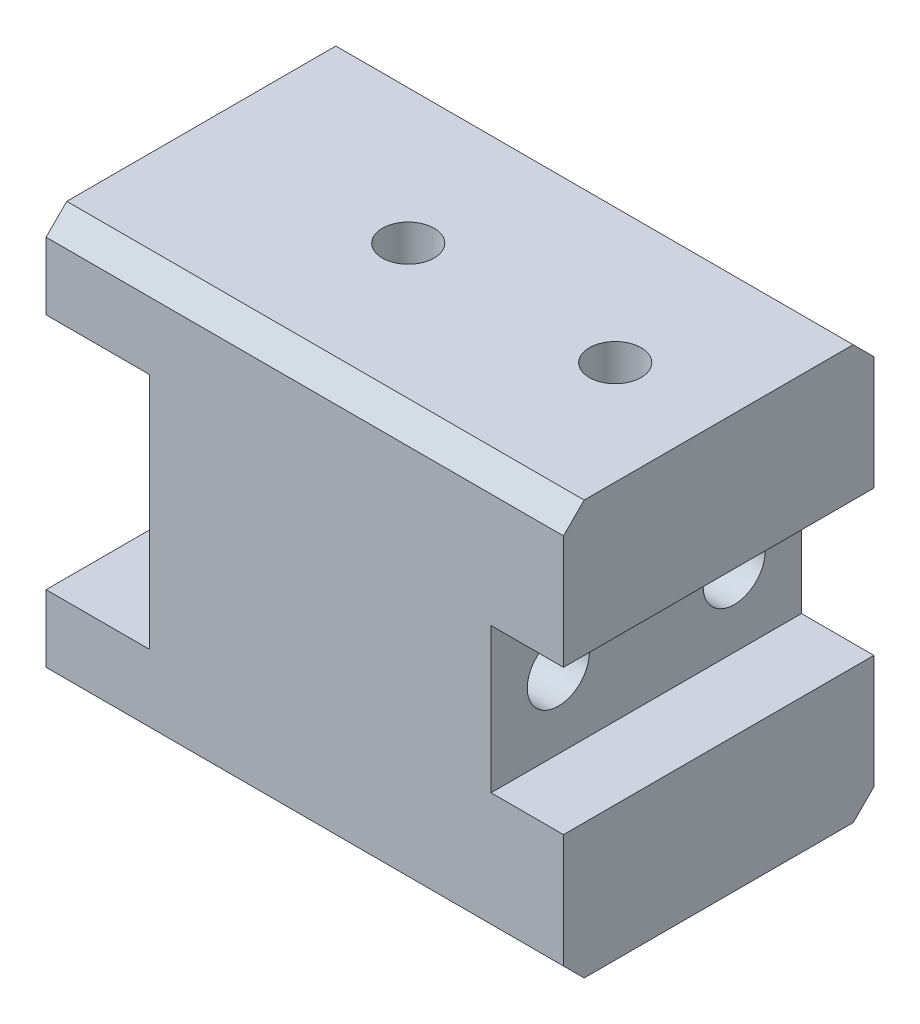
SolidWorks part; units mm, degrees
ref_plane "Front" through (0, 0, 0) normal (0, 0, 1) x (1, 0, 0)
ref_plane "Top" through (0, 0, 0) normal (0, 1, 0) x (1, 0, 0)
ref_plane "Right" through (0, 0, 0) normal (1, 0, 0) x (0, 0, -1)
sketch "草图1" plane through (0, 0, 0) normal (1, 0, 0) x (0, 0, -1)
  line L1 (7.5, -10) -> (-7.5, -10)
  line L2 (7.5, -10) -> (7.5, 10)
  line L3 (7.5, 10) -> (-7.5, 10)
  line L4 (-7.5, -10) -> (-7.5, 10)
  line L5 (7.5, -10) -> (-7.5, 10) construction
  line L6 (7.5, 10) -> (-7.5, -10) construction
  point P0 (0, 0)
  dimension "D1" = 15
  dimension "D2" = 20
extrude "凸台-拉伸1" add sketch "草图1" along normal blind 25
sketch "草图2" plane through (0, 0, 0) normal (-1, 0, 0) x (0, 0, 1)
  line L0 (-7.5, 0) -> (7.5, 0) construction
  line L1 (-7.5, -10) -> (-7.5, 10) construction
  line L2 (7.5, 10) -> (7.5, -10) construction
  line L4 (7.5, -5.75) -> (-7.5, -5.75)
  line L5 (7.5, -5.75) -> (7.5, 5.75)
  line L6 (7.5, 5.75) -> (-7.5, 5.75)
  line L7 (-7.5, -5.75) -> (-7.5, 5.75)
  line L8 (7.5, -5.75) -> (-7.5, 5.75) construction
  line L9 (7.5, 5.75) -> (-7.5, -5.75) construction
  point P6 (0, 0)
  dimension "D1" = 11.5
extrude "切除-拉伸1" cut sketch "草图2" against normal blind 5
sketch "草图3" plane through (5, 0, 0) normal (-1, 0, 0) x (0, 0, 1)
  line L0 (-7.5, 0) -> (7.5, 0) construction
  line L1 (-7.5, 5.75) -> (-7.5, -5.75) construction
  line L2 (7.5, -5.75) -> (7.5, 5.75) construction
  line L3 (0, 5.75) -> (0, -5.75) construction
  line L4 (7.5, 5.75) -> (-7.5, 5.75) construction
  line L5 (-7.5, -5.75) -> (7.5, -5.75) construction
  circle A0 centre (-4.25, 0) radius 1.5
  circle A1 centre (4.25, 0) radius 1.5
  dimension "D1" = 3
  dimension "D2" = 3
  dimension "D3" = 8.5
extrude "切除-拉伸2" cut sketch "草图3" against normal through all
sketch "草图4" plane through (0, 10, 0) normal (0, 1, 0) x (1, 0, 0)
  line L0 (25, 0) -> (0, 0) construction
  line L1 (25, 7.5) -> (25, -7.5) construction
  line L2 (0, 7.5) -> (0, -7.5) construction
  circle A0 centre (20, 0) radius 1.25
  circle A1 centre (10, 0) radius 1.25
  dimension "D1" = 2.5
  dimension "D2" = 2.5
  dimension "D3" = 10
  dimension "D4" = 5
extrude "切除-拉伸3" cut sketch "草图4" against normal through all
chamfer "倒角1" distance 1 angle 45 4 edges at (12.5, -10, -7.5) (12.5, -10, 7.5) (12.5, 10, -7.5) (12.5, 10, 7.5)
sketch "草图5" plane through (25, 0, 0) normal (1, 0, 0) x (0, 0, -1)
  line L0 (-7.5, 9) -> (-7.5, -9) construction
  line L1 (7.5, -3.5) -> (-7.5, -3.5)
  line L2 (7.5, -3.5) -> (7.5, 3.5)
  line L3 (7.5, 3.5) -> (-7.5, 3.5)
  line L4 (-7.5, -3.5) -> (-7.5, 3.5)
  line L5 (7.5, -3.5) -> (-7.5, 3.5) construction
  line L6 (7.5, 3.5) -> (-7.5, -3.5) construction
  point P0 (0, 0)
  dimension "D1" = 7
extrude "切除-拉伸4" cut sketch "草图5" against normal blind 3.5
